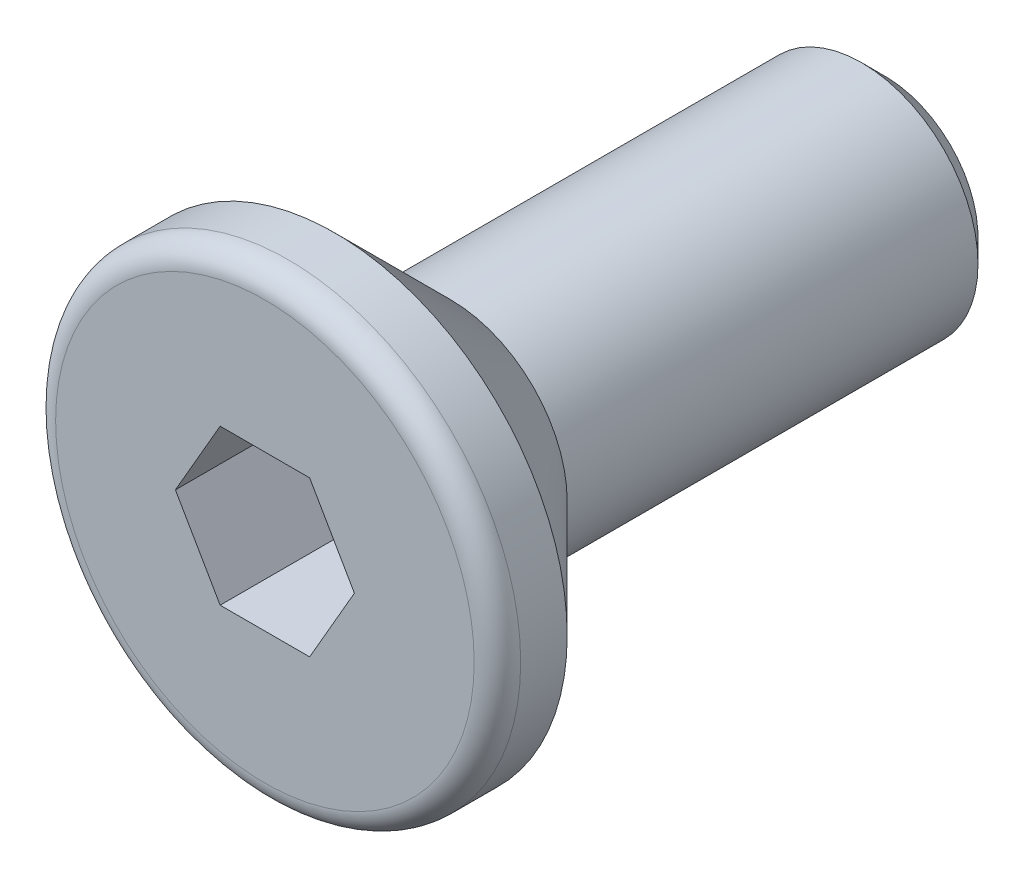
SolidWorks part; units mm, degrees
ref_plane "前视基准面" through (0, 0, 0) normal (0, 0, 1) x (1, 0, 0)
ref_plane "上视基准面" through (0, 0, 0) normal (0, 1, 0) x (1, 0, 0)
ref_plane "右视基准面" through (0, 0, 0) normal (1, 0, 0) x (0, 0, -1)
sketch "草图1" plane through (0, 0, 0) normal (1, 0, 0) x (0, 0, -1)
  line L0 (-4, 0) -> (-4, 3)
  line L1 (-4, 3) -> (-3.1, 3)
  line L2 (-3.1, 3) -> (-1.6, 1.5)
  line L3 (-1.6, 1.5) -> (3.7, 1.5)
  line L4 (3.7, 1.5) -> (4, 1.2)
  line L5 (4, 1.2) -> (4, 0)
  line L6 (4, 0) -> (-4, 0)
  dimension "D1" = 8
  dimension "D2" = 3
  dimension "D3" = 45
  dimension "D4" = 0.3
  dimension "D5" = 2.4
  dimension "D6" = 1.5
revolve "旋转1" add sketch "草图1" angle 360 about L6
sketch "草图2" plane through (0, 0, 4) normal (0, 0, 1) x (1, 0, 0)
  line L1 (1.1547, 0) -> (0.5774, 1)
  line L2 (0.5774, 1) -> (-0.5774, 1)
  line L3 (-0.5774, 1) -> (-1.1547, 0)
  line L4 (-1.1547, 0) -> (-0.5774, -1)
  line L5 (-0.5774, -1) -> (0.5774, -1)
  line L6 (0.5774, -1) -> (1.1547, 0)
  circle A0 centre (0, 0) radius 1 construction
  dimension "D1" = 2
extrude "切除-拉伸1" cut sketch "草图2" against normal blind 1.5
fillet "圆角1" radius 0.3 1 edges at (-3, 0, 4)
